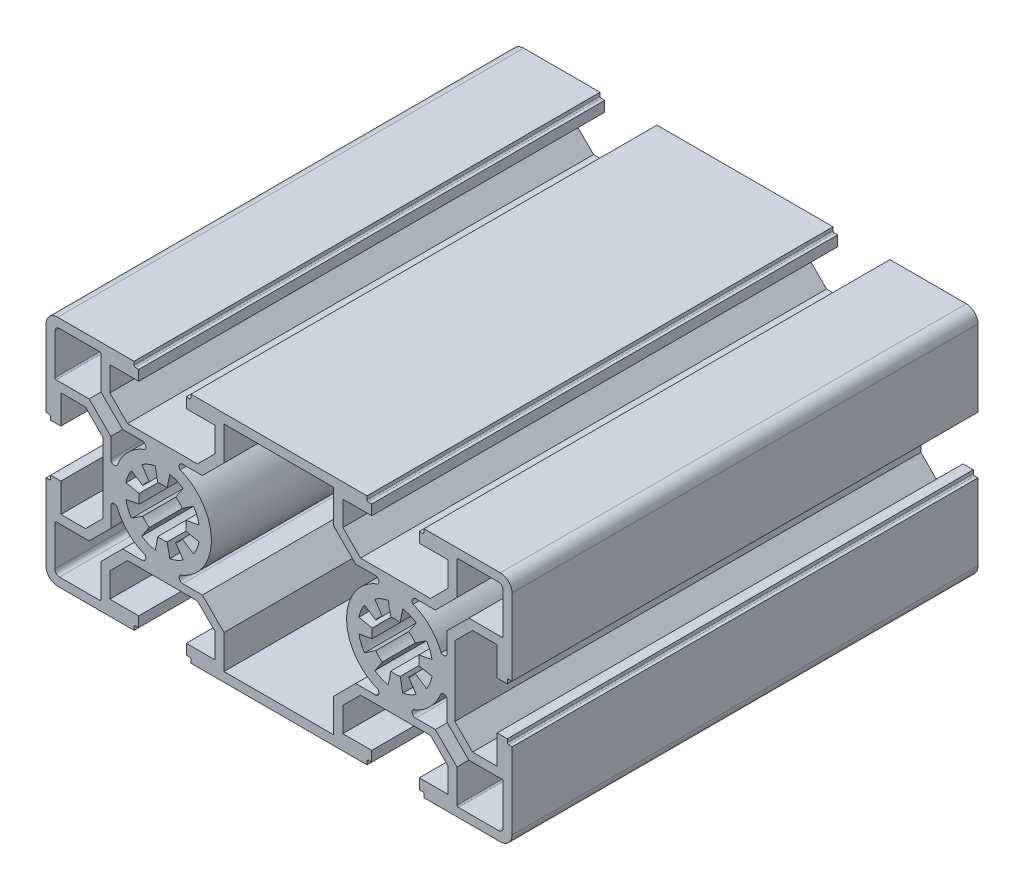
SolidWorks part; units mm, degrees
ref_plane "前视基准面" through (0, 0, 0) normal (0, 0, 1) x (1, 0, 0)
ref_plane "上视基准面" through (0, 0, 0) normal (0, 1, 0) x (1, 0, 0)
ref_plane "右视基准面" through (0, 0, 0) normal (1, 0, 0) x (0, 0, -1)
sketch "草图1" plane through (0, 0, 0) normal (0, 0, 1) x (1, 0, 0)
  line L0 (-30.9772, 25.1514) -> (-47.3772, 25.1514)
  line L1 (-49.8772, 22.6514) -> (-49.8772, 6.2514)
  line L2 (-38.0772, 15.897) -> (-38.0772, 22.9514)
  line L3 (-38.3772, 23.2514) -> (-46.9772, 23.2514)
  line L4 (-47.9772, 22.2514) -> (-47.9772, 13.6514)
  line L5 (-47.6772, 13.3514) -> (-40.6228, 13.3514)
  line L6 (-29.9772, 21.9514) -> (-36.1772, 21.9514)
  line L7 (-29.9772, 24.1514) -> (-30.6772, 24.1514)
  line L8 (-30.9772, 24.4514) -> (-30.9772, 25.1514)
  line L9 (-49.8772, 6.2514) -> (-49.1772, 6.2514)
  line L10 (-48.8772, 5.9514) -> (-48.8772, 5.2514)
  line L11 (-36.1772, 21.9514) -> (-36.1772, 16.684)
  line L12 (-29.9772, 24.1514) -> (-29.9772, 21.9514)
  line L13 (-35.9772, 4.4835) -> (-35.9772, 8.7058)
  line L14 (-29.3218, -6.5004) -> (-27.7106, -4.0891)
  line L15 (-26.4379, -7.6949) -> (-25.8722, -4.8506)
  line L16 (-23.3165, -7.6949) -> (-23.8822, -4.8506)
  line L17 (-20.4326, -6.5004) -> (-22.0438, -4.0891)
  line L18 (-18.2254, -4.2932) -> (-20.6367, -2.682)
  line L19 (-17.0309, -1.4093) -> (-19.8752, -0.8436)
  line L20 (-17.0309, 1.7121) -> (-19.8752, 1.1464)
  line L21 (-18.2254, 4.596) -> (-20.6367, 2.9848)
  line L22 (-20.4326, 6.8032) -> (-22.0438, 4.3919)
  line L23 (-23.3165, 7.9977) -> (-23.8822, 5.1534)
  line L24 (-26.4379, 7.9977) -> (-25.8722, 5.1534)
  line L25 (-29.3218, 6.8032) -> (-27.7106, 4.3919)
  line L26 (-31.529, 4.596) -> (-29.1177, 2.9848)
  line L27 (-32.7235, 1.7121) -> (-29.8792, 1.1464)
  line L28 (-32.7235, -1.4093) -> (-29.8792, -0.8436)
  line L29 (-31.529, -4.2932) -> (-29.1177, -2.682)
  line L30 (-40.6228, 13.3514) -> (-35.9772, 8.7058)
  line L31 (-36.1772, 16.684) -> (-32.3772, 12.884)
  line L32 (-38.0772, 15.897) -> (-33.4316, 11.2514)
  line L33 (-29.2093, 11.2514) -> (-33.4316, 11.2514)
  line L34 (-24.8772, 12.884) -> (-32.3772, 12.884)
  line L35 (-18.7772, 25.1514) -> (2.6228, 25.1514)
  line L36 (-11.6772, 23.1514) -> (2.6228, 23.1514)
  line L37 (-19.7772, 21.9514) -> (-13.5772, 21.9514)
  line L38 (-19.7772, 24.1514) -> (-19.0772, 24.1514)
  line L39 (-18.7772, 24.4514) -> (-18.7772, 25.1514)
  line L40 (-13.5772, 21.9514) -> (-13.5772, 16.684)
  line L41 (-11.6772, 23.1514) -> (-11.6772, 15.897)
  line L42 (-19.7772, 24.1514) -> (-19.7772, 21.9514)
  line L43 (-13.5772, 16.684) -> (-17.3772, 12.884)
  line L44 (-11.6772, 15.897) -> (-16.3228, 11.2514)
  line L45 (-20.5451, 11.2514) -> (-16.3228, 11.2514)
  line L46 (-24.8772, 12.884) -> (-17.3772, 12.884)
  line L47 (-30.9772, -24.8486) -> (-47.3772, -24.8486)
  line L48 (-49.8772, -22.3486) -> (-49.8772, -5.9486)
  line L49 (-38.0772, -15.5942) -> (-38.0772, -22.6486)
  line L50 (-38.3772, -22.9486) -> (-46.9772, -22.9486)
  line L51 (-47.9772, -21.9486) -> (-47.9772, -13.3486)
  line L52 (-47.6772, -13.0486) -> (-40.6228, -13.0486)
  line L53 (-29.9772, -23.8486) -> (-30.6772, -23.8486)
  line L54 (-30.9772, -24.1486) -> (-30.9772, -24.8486)
  line L55 (-49.8772, -5.9486) -> (-49.1772, -5.9486)
  line L56 (-48.8772, -5.6486) -> (-48.8772, -4.9486)
  line L57 (-35.9772, -4.1807) -> (-35.9772, -8.403)
  line L58 (-40.6228, -13.0486) -> (-35.9772, -8.403)
  line L59 (-38.0772, -15.5942) -> (-33.4316, -10.9486)
  line L60 (-29.2093, -10.9486) -> (-33.4316, -10.9486)
  line L61 (-18.7772, -24.8486) -> (2.6228, -24.8486)
  line L62 (-19.7772, -23.8486) -> (-19.0772, -23.8486)
  line L63 (-18.7772, -24.1486) -> (-18.7772, -24.8486)
  line L64 (-11.6772, -15.5942) -> (-16.3228, -10.9486)
  line L65 (-20.5451, -10.9486) -> (-16.3228, -10.9486)
  line L66 (-29.9772, -21.6486) -> (-36.1772, -21.6486)
  line L67 (-36.1772, -21.6486) -> (-36.1772, -16.3812)
  line L68 (-29.9772, -23.8486) -> (-29.9772, -21.6486)
  line L69 (-36.1772, -16.3812) -> (-32.3772, -12.5812)
  line L70 (-24.8772, -12.5812) -> (-32.3772, -12.5812)
  line L71 (-19.7772, -21.6486) -> (-13.5772, -21.6486)
  line L72 (-13.5772, -21.6486) -> (-13.5772, -16.3812)
  line L73 (-19.7772, -23.8486) -> (-19.7772, -21.6486)
  line L74 (-13.5772, -16.3812) -> (-17.3772, -12.5812)
  line L75 (-24.8772, -12.5812) -> (-17.3772, -12.5812)
  line L76 (-46.6772, 5.2514) -> (-46.6772, 11.4514)
  line L77 (-46.6772, 11.4514) -> (-41.4098, 11.4514)
  line L78 (-48.8772, 5.2514) -> (-46.6772, 5.2514)
  line L79 (-41.4098, 11.4514) -> (-37.6098, 7.6514)
  line L80 (-37.6098, 0.1514) -> (-37.6098, 7.6514)
  line L81 (-46.6772, -4.9486) -> (-46.6772, -11.1486)
  line L82 (-46.6772, -11.1486) -> (-41.4098, -11.1486)
  line L83 (-48.8772, -4.9486) -> (-46.6772, -4.9486)
  line L84 (-41.4098, -11.1486) -> (-37.6098, -7.3486)
  line L85 (-37.6098, 0.1514) -> (-37.6098, -7.3486)
  line L86 (19.0228, 25.1514) -> (2.6228, 25.1514)
  line L87 (11.8228, 23.1514) -> (2.6228, 23.1514)
  line L88 (20.0228, 21.9514) -> (13.8228, 21.9514)
  line L89 (20.0228, 24.1514) -> (19.3228, 24.1514)
  line L90 (19.0228, 24.4514) -> (19.0228, 25.1514)
  line L91 (13.8228, 21.9514) -> (13.8228, 16.684)
  line L92 (11.8228, 23.1514) -> (11.8228, 15.997)
  line L93 (20.0228, 24.1514) -> (20.0228, 21.9514)
  line L94 (20.6782, -6.5004) -> (22.2894, -4.0891)
  line L95 (23.5621, -7.6949) -> (24.1278, -4.8506)
  line L96 (26.6835, -7.6949) -> (26.1178, -4.8506)
  line L97 (29.5674, -6.5004) -> (27.9562, -4.0891)
  line L98 (31.7746, -4.2932) -> (29.3633, -2.682)
  line L99 (32.9691, -1.4093) -> (30.1248, -0.8436)
  line L100 (32.9691, 1.7121) -> (30.1248, 1.1464)
  line L101 (31.7746, 4.596) -> (29.3633, 2.9848)
  line L102 (29.5674, 6.8032) -> (27.9562, 4.3919)
  line L103 (26.6835, 7.9977) -> (26.1178, 5.1534)
  line L104 (23.5621, 7.9977) -> (24.1278, 5.1534)
  line L105 (20.6782, 6.8032) -> (22.2894, 4.3919)
  line L106 (18.471, 4.596) -> (20.8823, 2.9848)
  line L107 (17.2765, 1.7121) -> (20.1208, 1.1464)
  line L108 (17.2765, -1.4093) -> (20.1208, -0.8436)
  line L109 (18.471, -4.2932) -> (20.8823, -2.682)
  line L110 (13.8228, 16.684) -> (17.6228, 12.884)
  line L111 (11.8228, 15.997) -> (16.5684, 11.2514)
  line L112 (20.7907, 11.2514) -> (16.5684, 11.2514)
  line L113 (25.1228, 12.884) -> (17.6228, 12.884)
  line L114 (31.2228, 25.1514) -> (47.6228, 25.1514)
  line L115 (50.1228, 22.6514) -> (50.1228, 6.2514)
  line L116 (38.3228, 15.897) -> (38.3228, 22.9514)
  line L117 (38.6228, 23.2514) -> (47.2228, 23.2514)
  line L118 (48.2228, 22.2514) -> (48.2228, 13.6514)
  line L119 (47.9228, 13.3514) -> (40.8684, 13.3514)
  line L120 (30.2228, 21.9514) -> (36.4228, 21.9514)
  line L121 (30.2228, 24.1514) -> (30.9228, 24.1514)
  line L122 (31.2228, 24.4514) -> (31.2228, 25.1514)
  line L123 (50.1228, 6.2514) -> (49.4228, 6.2514)
  line L124 (49.1228, 5.9514) -> (49.1228, 5.2514)
  line L125 (36.4228, 21.9514) -> (36.4228, 16.684)
  line L126 (30.2228, 24.1514) -> (30.2228, 21.9514)
  line L127 (36.2228, 4.4835) -> (36.2228, 8.7058)
  line L128 (40.8684, 13.3514) -> (36.2228, 8.7058)
  line L129 (36.4228, 16.684) -> (32.6228, 12.884)
  line L130 (38.3228, 15.897) -> (33.6772, 11.2514)
  line L131 (29.4549, 11.2514) -> (33.6772, 11.2514)
  line L132 (25.1228, 12.884) -> (32.6228, 12.884)
  line L133 (19.0228, -24.8486) -> (2.6228, -24.8486)
  line L134 (20.0228, -23.8486) -> (19.3228, -23.8486)
  line L135 (19.0228, -24.1486) -> (19.0228, -24.8486)
  line L136 (11.8228, -15.6942) -> (16.5684, -10.9486)
  line L137 (20.7907, -10.9486) -> (16.5684, -10.9486)
  line L138 (31.2228, -24.8486) -> (47.6228, -24.8486)
  line L139 (50.1228, -22.3486) -> (50.1228, -5.9486)
  line L140 (38.3228, -15.5942) -> (38.3228, -22.6486)
  line L141 (38.6228, -22.9486) -> (47.2228, -22.9486)
  line L142 (48.2228, -21.9486) -> (48.2228, -13.3486)
  line L143 (47.9228, -13.0486) -> (40.8684, -13.0486)
  line L144 (30.2228, -23.8486) -> (30.9228, -23.8486)
  line L145 (31.2228, -24.1486) -> (31.2228, -24.8486)
  line L146 (50.1228, -5.9486) -> (49.4228, -5.9486)
  line L147 (49.1228, -5.6486) -> (49.1228, -4.9486)
  line L148 (36.2228, -4.1807) -> (36.2228, -8.403)
  line L149 (40.8684, -13.0486) -> (36.2228, -8.403)
  line L150 (38.3228, -15.5942) -> (33.6772, -10.9486)
  line L151 (29.4549, -10.9486) -> (33.6772, -10.9486)
  line L152 (20.0228, -21.6486) -> (13.8228, -21.6486)
  line L153 (13.8228, -21.6486) -> (13.8228, -16.3812)
  line L154 (20.0228, -23.8486) -> (20.0228, -21.6486)
  line L155 (13.8228, -16.3812) -> (17.6228, -12.5812)
  line L156 (25.1228, -12.5812) -> (17.6228, -12.5812)
  line L157 (30.2228, -21.6486) -> (36.4228, -21.6486)
  line L158 (36.4228, -21.6486) -> (36.4228, -16.3812)
  line L159 (30.2228, -23.8486) -> (30.2228, -21.6486)
  line L160 (36.4228, -16.3812) -> (32.6228, -12.5812)
  line L161 (25.1228, -12.5812) -> (32.6228, -12.5812)
  line L162 (46.9228, 5.2514) -> (46.9228, 11.4514)
  line L163 (46.9228, 11.4514) -> (41.6554, 11.4514)
  line L164 (49.1228, 5.2514) -> (46.9228, 5.2514)
  line L165 (41.6554, 11.4514) -> (37.8554, 7.6514)
  line L166 (37.8554, 0.1514) -> (37.8554, 7.6514)
  line L167 (46.9228, -4.9486) -> (46.9228, -11.1486)
  line L168 (46.9228, -11.1486) -> (41.6554, -11.1486)
  line L169 (49.1228, -4.9486) -> (46.9228, -4.9486)
  line L170 (41.6554, -11.1486) -> (37.8554, -7.3486)
  line L171 (37.8554, 0.1514) -> (37.8554, -7.3486)
  line L172 (-11.6772, -22.8486) -> (2.6228, -22.8486)
  line L173 (-11.6772, -22.8486) -> (-11.6772, -15.5942)
  line L174 (11.8228, -22.8486) -> (2.6228, -22.8486)
  line L175 (11.8228, -22.8486) -> (11.8228, -15.6942)
  arc A0 (-47.3772, 25.1514) -> (-49.8772, 22.6514) centre (-47.3772, 22.6514) ccw
  arc A1 (-38.0772, 22.9514) -> (-38.3772, 23.2514) centre (-38.3772, 22.9514) ccw
  arc A2 (-46.9772, 23.2514) -> (-47.9772, 22.2514) centre (-46.9772, 22.2514) ccw
  arc A3 (-47.9772, 13.6514) -> (-47.6772, 13.3514) centre (-47.6772, 13.6514) ccw
  arc A4 (-30.9772, 24.4514) -> (-30.6772, 24.1514) centre (-30.6772, 24.4514) ccw
  arc A5 (-48.8772, 5.9514) -> (-49.1772, 6.2514) centre (-49.1772, 5.9514) ccw
  arc A6 (-25.8722, -4.8506) -> (-23.8822, -4.8506) centre (-24.8772, 0.1514) ccw
  arc A7 (-22.0438, -4.0891) -> (-20.6367, -2.682) centre (-24.8772, 0.1514) ccw
  arc A8 (-19.8752, -0.8436) -> (-19.8752, 1.1464) centre (-24.8772, 0.1514) ccw
  arc A9 (-20.6367, 2.9848) -> (-22.0438, 4.3919) centre (-24.8772, 0.1514) ccw
  arc A10 (-23.8822, 5.1534) -> (-25.8722, 5.1534) centre (-24.8772, 0.1514) ccw
  arc A11 (-27.7106, 4.3919) -> (-29.1177, 2.9848) centre (-24.8772, 0.1514) ccw
  arc A12 (-29.8792, 1.1464) -> (-29.8792, -0.8436) centre (-24.8772, 0.1514) ccw
  arc A13 (-29.1177, -2.682) -> (-27.7106, -4.0891) centre (-24.8772, 0.1514) ccw
  arc A14 (-29.3218, -6.5004) -> (-26.4379, -7.6949) centre (-24.8772, 0.1514) ccw
  arc A15 (-23.3165, -7.6949) -> (-20.4326, -6.5004) centre (-24.8772, 0.1514) ccw
  arc A16 (-18.2254, -4.2932) -> (-17.0309, -1.4093) centre (-24.8772, 0.1514) ccw
  arc A17 (-17.0309, 1.7121) -> (-18.2254, 4.596) centre (-24.8772, 0.1514) ccw
  arc A18 (-20.4326, 6.8032) -> (-23.3165, 7.9977) centre (-24.8772, 0.1514) ccw
  arc A19 (-26.4379, 7.9977) -> (-29.3218, 6.8032) centre (-24.8772, 0.1514) ccw
  arc A20 (-31.529, 4.596) -> (-32.7235, 1.7121) centre (-24.8772, 0.1514) ccw
  arc A21 (-32.7235, -1.4093) -> (-31.529, -4.2932) centre (-24.8772, 0.1514) ccw
  arc A22 (-28.6618, 9.9456) -> (-34.6714, 3.936) centre (-24.8772, 0.1514) ccw
  arc A23 (-35.9772, 4.4835) -> (-34.6714, 3.936) centre (-35.2095, 4.4835) ccw
  arc A24 (-28.6618, 9.9456) -> (-29.2093, 11.2514) centre (-29.2093, 10.4837) ccw
  arc A25 (-19.0772, 24.1514) -> (-18.7772, 24.4514) centre (-19.0772, 24.4514) ccw
  arc A26 (-15.083, 3.936) -> (-21.0926, 9.9456) centre (-24.8772, 0.1514) ccw
  arc A27 (-20.5451, 11.2514) -> (-21.0926, 9.9456) centre (-20.5451, 10.4837) ccw
  arc A28 (-49.8772, -22.3486) -> (-47.3772, -24.8486) centre (-47.3772, -22.3486) ccw
  arc A29 (-38.3772, -22.9486) -> (-38.0772, -22.6486) centre (-38.3772, -22.6486) ccw
  arc A30 (-47.9772, -21.9486) -> (-46.9772, -22.9486) centre (-46.9772, -21.9486) ccw
  arc A31 (-47.6772, -13.0486) -> (-47.9772, -13.3486) centre (-47.6772, -13.3486) ccw
  arc A32 (-30.6772, -23.8486) -> (-30.9772, -24.1486) centre (-30.6772, -24.1486) ccw
  arc A33 (-49.1772, -5.9486) -> (-48.8772, -5.6486) centre (-49.1772, -5.6486) ccw
  arc A34 (-34.6714, -3.6332) -> (-28.6618, -9.6428) centre (-24.8772, 0.1514) ccw
  arc A35 (-34.6714, -3.6332) -> (-35.9772, -4.1807) centre (-35.2095, -4.1807) ccw
  arc A36 (-29.2093, -10.9486) -> (-28.6618, -9.6428) centre (-29.2093, -10.1809) ccw
  arc A37 (-18.7772, -24.1486) -> (-19.0772, -23.8486) centre (-19.0772, -24.1486) ccw
  arc A38 (-21.0926, -9.6428) -> (-15.083, 3.936) centre (-24.8772, 0.1514) ccw
  arc A39 (-21.0926, -9.6428) -> (-20.5451, -10.9486) centre (-20.5451, -10.1809) ccw
  arc A40 (19.0228, 24.4514) -> (19.3228, 24.1514) centre (19.3228, 24.4514) ccw
  arc A41 (24.1278, -4.8506) -> (26.1178, -4.8506) centre (25.1228, 0.1514) ccw
  arc A42 (27.9562, -4.0891) -> (29.3633, -2.682) centre (25.1228, 0.1514) ccw
  arc A43 (30.1248, -0.8436) -> (30.1248, 1.1464) centre (25.1228, 0.1514) ccw
  arc A44 (29.3633, 2.9848) -> (27.9562, 4.3919) centre (25.1228, 0.1514) ccw
  arc A45 (26.1178, 5.1534) -> (24.1278, 5.1534) centre (25.1228, 0.1514) ccw
  arc A46 (22.2894, 4.3919) -> (20.8823, 2.9848) centre (25.1228, 0.1514) ccw
  arc A47 (20.1208, 1.1464) -> (20.1208, -0.8436) centre (25.1228, 0.1514) ccw
  arc A48 (20.8823, -2.682) -> (22.2894, -4.0891) centre (25.1228, 0.1514) ccw
  arc A49 (20.6782, -6.5004) -> (23.5621, -7.6949) centre (25.1228, 0.1514) ccw
  arc A50 (26.6835, -7.6949) -> (29.5674, -6.5004) centre (25.1228, 0.1514) ccw
  arc A51 (31.7746, -4.2932) -> (32.9691, -1.4093) centre (25.1228, 0.1514) ccw
  arc A52 (32.9691, 1.7121) -> (31.7746, 4.596) centre (25.1228, 0.1514) ccw
  arc A53 (29.5674, 6.8032) -> (26.6835, 7.9977) centre (25.1228, 0.1514) ccw
  arc A54 (23.5621, 7.9977) -> (20.6782, 6.8032) centre (25.1228, 0.1514) ccw
  arc A55 (18.471, 4.596) -> (17.2765, 1.7121) centre (25.1228, 0.1514) ccw
  arc A56 (17.2765, -1.4093) -> (18.471, -4.2932) centre (25.1228, 0.1514) ccw
  arc A57 (21.3382, 9.9456) -> (15.3286, 3.936) centre (25.1228, 0.1514) ccw
  arc A58 (21.3382, 9.9456) -> (20.7907, 11.2514) centre (20.7907, 10.4837) ccw
  arc A59 (50.1228, 22.6514) -> (47.6228, 25.1514) centre (47.6228, 22.6514) ccw
  arc A60 (38.6228, 23.2514) -> (38.3228, 22.9514) centre (38.6228, 22.9514) ccw
  arc A61 (48.2228, 22.2514) -> (47.2228, 23.2514) centre (47.2228, 22.2514) ccw
  arc A62 (47.9228, 13.3514) -> (48.2228, 13.6514) centre (47.9228, 13.6514) ccw
  arc A63 (30.9228, 24.1514) -> (31.2228, 24.4514) centre (30.9228, 24.4514) ccw
  arc A64 (49.4228, 6.2514) -> (49.1228, 5.9514) centre (49.4228, 5.9514) ccw
  arc A65 (34.917, 3.936) -> (28.9074, 9.9456) centre (25.1228, 0.1514) ccw
  arc A66 (34.917, 3.936) -> (36.2228, 4.4835) centre (35.4551, 4.4835) ccw
  arc A67 (29.4549, 11.2514) -> (28.9074, 9.9456) centre (29.4549, 10.4837) ccw
  arc A68 (19.3228, -23.8486) -> (19.0228, -24.1486) centre (19.3228, -24.1486) ccw
  arc A69 (15.3286, 3.936) -> (21.3382, -9.6428) centre (25.1228, 0.1514) ccw
  arc A70 (20.7907, -10.9486) -> (21.3382, -9.6428) centre (20.7907, -10.1809) ccw
  arc A71 (47.6228, -24.8486) -> (50.1228, -22.3486) centre (47.6228, -22.3486) ccw
  arc A72 (38.3228, -22.6486) -> (38.6228, -22.9486) centre (38.6228, -22.6486) ccw
  arc A73 (47.2228, -22.9486) -> (48.2228, -21.9486) centre (47.2228, -21.9486) ccw
  arc A74 (48.2228, -13.3486) -> (47.9228, -13.0486) centre (47.9228, -13.3486) ccw
  arc A75 (31.2228, -24.1486) -> (30.9228, -23.8486) centre (30.9228, -24.1486) ccw
  arc A76 (49.1228, -5.6486) -> (49.4228, -5.9486) centre (49.4228, -5.6486) ccw
  arc A77 (28.9074, -9.6428) -> (34.917, -3.6332) centre (25.1228, 0.1514) ccw
  arc A78 (36.2228, -4.1807) -> (34.917, -3.6332) centre (35.4551, -4.1807) ccw
  arc A79 (28.9074, -9.6428) -> (29.4549, -10.9486) centre (29.4549, -10.1809) ccw
extrude "凸台-拉伸1" add sketch "草图1" along normal blind 100
